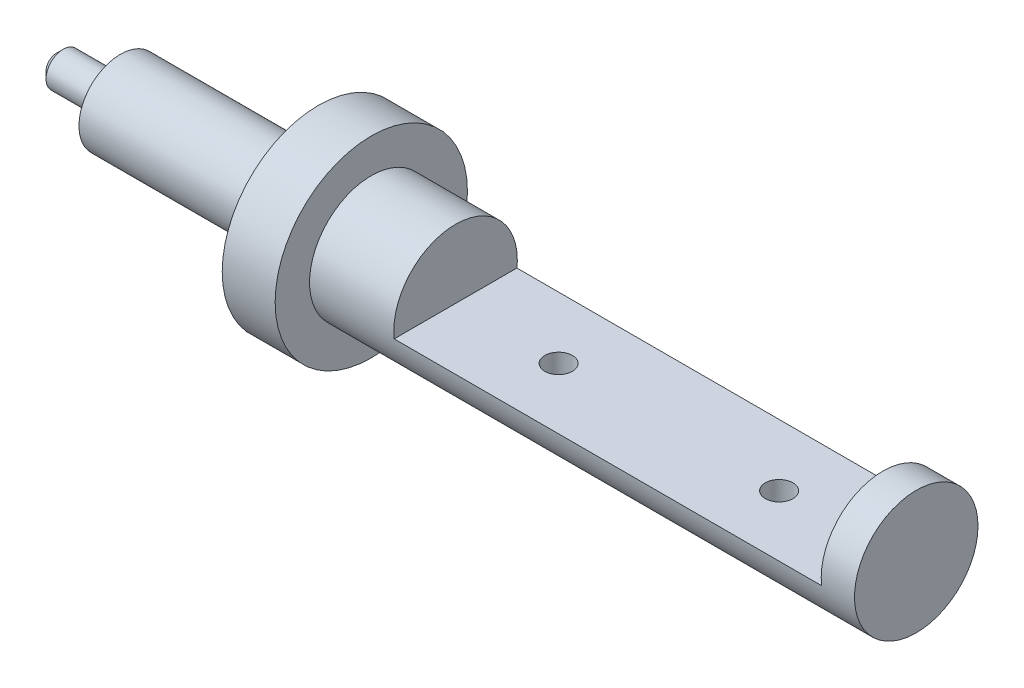
SolidWorks part; units mm, degrees
ref_plane "Front Plane" through (0, 0, 0) normal (0, 0, 1) x (1, 0, 0)
ref_plane "Top Plane" through (0, 0, 0) normal (0, 1, 0) x (1, 0, 0)
ref_plane "Right Plane" through (0, 0, 0) normal (1, 0, 0) x (0, 0, -1)
sketch "Sketch1" plane through (0, 0, 0) normal (0, 0, 1) x (1, 0, 0)
  line L0 (0, 0) -> (-60913.6921, 0) construction
  line L1 (0, 0) -> (0, 28)
  line L2 (0, 28) -> (-247.1, 28)
  line L3 (-247.1, 28) -> (-247.1, 43.6)
  line L4 (-247.1, 43.6) -> (-271.1, 43.6)
  line L5 (-271.1, 43.6) -> (-271.1, 18.75)
  line L6 (-271.1, 18.75) -> (-360.9, 18.75)
  line L7 (-360.9, 18.75) -> (-360.9, 7.7965)
  line L8 (-360.9, 7.7965) -> (-386.8, 7.7965)
  line L9 (-389.8, 4.7965) -> (-389.8, 0)
  line L10 (-389.8, 0) -> (0, 0)
  line L11 (-386.8, 7.7965) -> (-389.8, 4.7965)
  point P11 (-389.8, 7.7965)
  dimension "D1" = 28
  dimension "D2" = 247.1
  dimension "D3" = 43.6
  dimension "D4" = 89.8
  dimension "D5" = 28.9
  dimension "D6" = 18.75
  dimension "D7" = 24
  dimension "D8" = 3
  dimension "D9" = 45
  dimension "D10" = 386.8786
revolve "Revolve1" add sketch "Sketch1" angle 360 about L0
sketch "Sketch2" plane through (0, 0, 0) normal (0, 0, 1) x (1, 0, 0)
  line L0 (0, 0) -> (-50000, 0) construction
  line L2 (0, -3.1) -> (-50000, -3.1) construction
  line L4 (0, 28) -> (-247.1, 28) construction
  line L5 (-15.1, 28) -> (-15.1, -3.1)
  line L6 (-15.1, -3.1) -> (-208.9, -3.1)
  line L7 (-208.9, -3.1) -> (-208.9, 28)
  line L8 (-208.9, 28) -> (-15.1, 28)
  dimension "D1" = 31.1
  dimension "D2" = 15.1
  dimension "D3" = 193.8
extrude "Cut-Extrude1" cut sketch "Sketch2" against normal through all both and the other way through all
sketch "Sketch3" plane through (0, -3.1, 0) normal (0, 1, 0) x (1, 0, 0)
  line L0 (0, -0.1721) -> (-237.4169, -0.1721) construction
  line L1 (-15.1, 27.8279) -> (-208.9, 27.8279) construction
  line L2 (-208.9, -28) -> (-208.9, 28) construction
  circle A0 centre (-162, -0.1721) radius 6.25
  circle A1 centre (-62, -0.1721) radius 6.25
  dimension "D2" = 12.5
  dimension "D3" = 12.5
  dimension "D1" = 28
  dimension "D4" = 100
  dimension "D5" = 46.9
extrude "Cut-Extrude2" cut sketch "Sketch3" against normal through all both and the other way through all
sketch "Sketch4" plane through (-360.9, 0, 0) normal (-1, 0, 0) x (0, 0, 1)
  circle A0 centre (0, 0) radius 18.5
  dimension "D1" = 37
